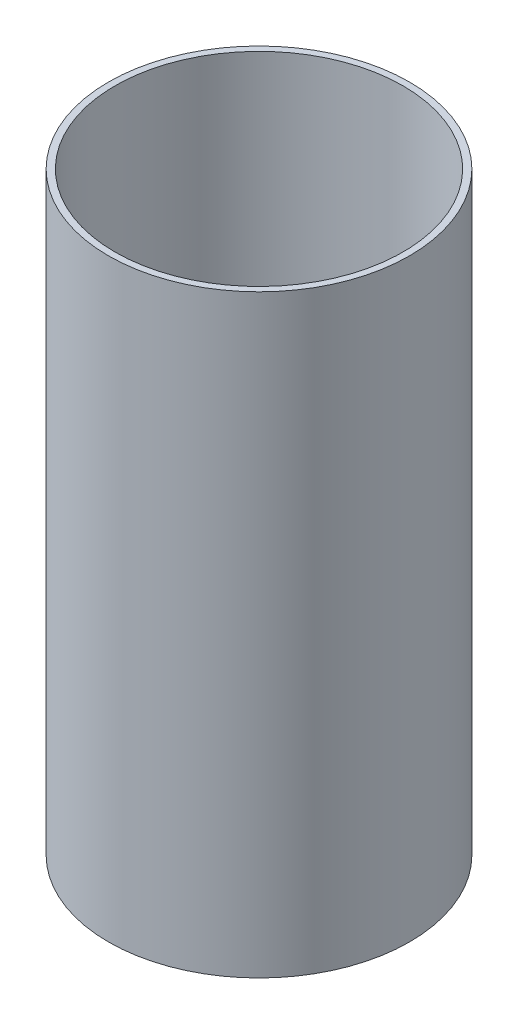
SolidWorks part; units mm, degrees
ref_plane "Plan de face" through (0, 0, 0) normal (0, 0, 1) x (1, 0, 0)
ref_plane "Plan de dessus" through (0, 0, 0) normal (0, 1, 0) x (1, 0, 0)
ref_plane "Plan de droite" through (0, 0, 0) normal (1, 0, 0) x (0, 0, -1)
sketch "Esquisse1" plane through (0, 0, 0) normal (0, 1, 0) x (1, 0, 0)
  circle A0 centre (0, 0) radius 76
  circle A1 centre (0, 0) radius 72.7
  dimension "D1" = 152
  dimension "D2" = 3.3
extrude "Boss.-Extru.1" add sketch "Esquisse1" along normal blind 300
ref_plane "Plan1" through (0, 150, 0) normal (0, -1, 0) x (-1, 0, 0)
